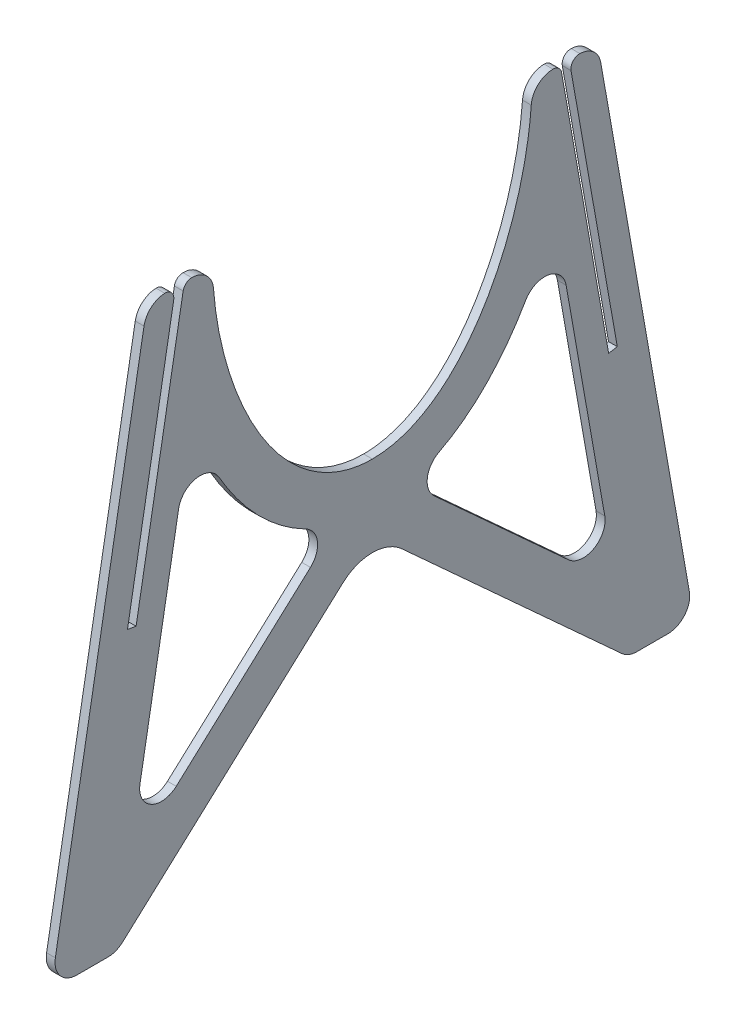
SolidWorks part; units mm, degrees
ref_plane "Front Plane" through (0, 0, 0) normal (0, 0, 1) x (1, 0, 0)
ref_plane "Top Plane" through (0, 0, 0) normal (0, 1, 0) x (1, 0, 0)
ref_plane "Right Plane" through (0, 0, 0) normal (1, 0, 0) x (0, 0, -1)
sketch "Sketch1" plane through (0, 0, 0) normal (1, 0, 0) x (0, 0, -1)
  line L0 (-36.5093, 0) -> (-51.5093, 0)
  line L1 (-51.5093, 0) -> (-73.5499, -124.9979)
  line L2 (-73.5499, -124.9979) -> (-58.5499, -124.9979)
  line L3 (0, -71.5821) -> (0, -56.5821)
  line L4 (-58.5499, -124.9979) -> (0, -71.5821)
  line L5 (-55.7055, -108.8666) -> (-8.1995, -65.5263)
  line L6 (-66.0499, -124.9979) -> (-44.0093, 0)
  line L7 (-36.5093, 0) -> (-58.5499, -124.9979)
  line L8 (-56.0144, -62.3253) -> (-54.0448, -62.6726)
  line L9 (-54.0448, -62.6726) -> (-42.9939, 0)
  line L10 (-56.0144, -62.3253) -> (-45.0248, 0)
  spline S0 degree 3 poles (-77.7959, -1999.3847) (-32.4836, 23.8711) (-36.7485, -12.4264) (-36.491, 1.5545) (-36.4661, 2.3494) (-36.4306, 3.1572) (-36.3845, 3.9779) (-36.3276, 4.8112) (-36.2596, 5.6568) (-36.1803, 6.5147) (-36.0895, 7.3844) (-35.9869, 8.2658) (-35.7244, 10.312) (-35.1824, 13.633) (-34.2081, 18.0418) (-32.9585, 22.5307) (-31.4871, 26.8758) (-29.7361, 31.19) (-27.7618, 35.3053) (-25.8567, 38.6677) (-24.1961, 41.2288) (-22.3532, 43.8233) (-19.9546, 46.7434) (-17.1663, 49.4666) (-14.8116, 51.366) (-12.8696, 52.7039) (-10.9306, 53.826) (-9.3257, 54.5881) (-8.076, 55.0896) (-7.1804, 55.4088) (-6.2832, 55.689) (-5.3849, 55.9304) (-4.4861, 56.1334) (-3.5872, 56.2984) (-2.6887, 56.4261) (-1.7912, 56.516) (18.7961, 57.7449) (5.3862, 31.1714) (1996.4181, 173.8153) knots -0.496353 -0.496353 -0.496353 -0.496353 0.010464 0.02111 0.03194 0.042952 0.054146 0.06552 0.077074 0.088806 0.100716 0.1128 0.125057 0.184996 0.250193 0.309425 0.375282 0.437501 0.499532 0.561635 0.595235 0.624194 0.69163 0.749302 0.783083 0.815122 0.84555 0.874512 0.887615 0.900555 0.913346 0.926005 0.938545 0.950983 0.963332 0.975609 0.987827 1.783802 1.783802 1.783802 1.783802 only from (-36.5093, 0) to (0, 56.5821)
  spline S1 degree 3 poles (-1998.8254, 118.855) (1.0133, 45.7594) (-12.3743, 56.9812) (0.9426, 56.5638) (1.4145, 56.5391) (1.8869, 56.5041) (2.3597, 56.459) (2.8328, 56.4036) (3.3061, 56.3379) (3.7796, 56.2618) (4.2531, 56.1753) (4.7267, 56.0782) (5.2003, 55.9706) (5.6737, 55.8523) (6.1469, 55.7234) (6.6198, 55.5837) (7.0925, 55.4333) (7.5646, 55.2719) (8.0363, 55.0998) (8.5074, 54.9167) (9.4771, 54.5166) (10.9487, 53.8166) (12.8926, 52.6895) (14.8396, 51.3453) (17.1949, 49.441) (19.9795, 46.7156) (22.3735, 43.7967) (24.2143, 41.2018) (25.8749, 38.6374) (27.7803, 35.2699) (29.7548, 31.1479) (31.5042, 26.8299) (32.9728, 22.484) (34.2165, 18.0065) (35.1851, 13.6164) (35.7638, 10.0694) (36.0753, 7.5493) (36.2369, 5.9585) (36.3605, 4.4083) (36.4465, 2.9002) (37.213, -19.7451) (26.3344, 23.0205) (116.0711, -1998.3604) knots -0.511405 -0.511405 -0.511405 -0.511405 0.006412 0.012834 0.019269 0.025719 0.032185 0.038671 0.045177 0.051706 0.058261 0.064843 0.071455 0.078099 0.084777 0.091492 0.098245 0.105039 0.111875 0.118757 0.125686 0.154729 0.185249 0.217392 0.25129 0.308883 0.376236 0.405202 0.438842 0.50101 0.563125 0.625443 0.691234 0.750428 0.815213 0.874806 0.897172 0.918949 0.940127 0.960698 0.980657 1.800718 1.800718 1.800718 1.800718 only from (0, 56.5821) to (36.5093, 0)
  spline S2 degree 3 poles (10989.6809, -475.2847) (-36.2394, -22.2542) (22.2831, -57.2917) (-0.9426, -56.5638) (-1.4145, -56.5391) (-1.8869, -56.5041) (-2.3597, -56.459) (-2.8328, -56.4036) (-3.3061, -56.3379) (-3.7796, -56.2618) (-4.2531, -56.1753) (-4.7267, -56.0782) (-5.2003, -55.9706) (-5.6737, -55.8523) (-6.1469, -55.7234) (-6.6198, -55.5837) (-7.0925, -55.4333) (-7.5646, -55.2719) (-8.0363, -55.0998) (-8.5074, -54.9167) (-9.4771, -54.5166) (-10.9487, -53.8166) (-12.8926, -52.6895) (-14.8396, -51.3453) (-17.1949, -49.441) (-19.9795, -46.7156) (-22.3735, -43.7967) (-24.2143, -41.2018) (-25.8749, -38.6374) (-27.7803, -35.2699) (-29.7548, -31.1479) (-31.5042, -26.8299) (-32.9728, -22.484) (-34.2165, -18.0065) (-35.1851, -13.6164) (-35.7638, -10.0694) (-36.0753, -7.5493) (-36.2369, -5.9585) (-36.3605, -4.4083) (-36.4465, -2.9002) (-37.7632, 36.0002) (-4.0465, -121.0006) (-537.3386, 10986.8499) knots -0.906271 -0.906271 -0.906271 -0.906271 0.006412 0.012834 0.019269 0.025719 0.032185 0.038671 0.045177 0.051706 0.058261 0.064843 0.071455 0.078099 0.084777 0.091492 0.098245 0.105039 0.111875 0.118757 0.125686 0.154729 0.185249 0.217392 0.25129 0.308883 0.376236 0.405202 0.438842 0.50101 0.563125 0.625443 0.691234 0.750428 0.815213 0.874806 0.897172 0.918949 0.940127 0.960698 0.980657 2.418461 2.418461 2.418461 2.418461 only from (0, -56.5821) to (-36.5093, 0)
  spline S3 degree 3 poles (77.7959, 1999.3847) (32.4836, -23.8711) (36.7485, 12.4264) (36.491, -1.5545) (36.4661, -2.3494) (36.4306, -3.1572) (36.3845, -3.9779) (36.3276, -4.8112) (36.2596, -5.6568) (36.1803, -6.5147) (36.0895, -7.3844) (35.9869, -8.2658) (35.7244, -10.312) (35.1824, -13.633) (34.2081, -18.0418) (32.9585, -22.5307) (31.4871, -26.8758) (29.7361, -31.19) (27.7618, -35.3053) (25.8567, -38.6677) (24.1961, -41.2288) (22.3532, -43.8233) (19.9546, -46.7434) (17.1663, -49.4666) (14.8116, -51.366) (12.8696, -52.7039) (10.9306, -53.826) (9.3257, -54.5881) (8.076, -55.0896) (7.1804, -55.4088) (6.2832, -55.689) (5.3849, -55.9304) (4.4861, -56.1334) (3.5872, -56.2984) (2.6887, -56.4261) (1.7912, -56.516) (-18.7961, -57.7449) (-5.3862, -31.1714) (-1996.4181, -173.8153) knots -0.496353 -0.496353 -0.496353 -0.496353 0.010464 0.02111 0.03194 0.042952 0.054146 0.06552 0.077074 0.088806 0.100716 0.1128 0.125057 0.184996 0.250193 0.309425 0.375282 0.437501 0.499532 0.561635 0.595235 0.624194 0.69163 0.749302 0.783083 0.815122 0.84555 0.874512 0.887615 0.900555 0.913346 0.926005 0.938545 0.950983 0.963332 0.975609 0.987827 1.783802 1.783802 1.783802 1.783802 only from (36.5093, 0) to (0, -56.5821)
  spline S4 degree 3 poles (36.5093, 0) (36.5093, -0.2338) (36.5066, -0.7092) (36.491, -1.5545) (36.4661, -2.3494) (36.4306, -3.1572) (36.3845, -3.9779) (36.3276, -4.8112) (36.2596, -5.6568) (36.1803, -6.5147) (36.0895, -7.3844) (35.9869, -8.2658) (35.7244, -10.312) (35.1824, -13.633) (34.2081, -18.0418) (32.9585, -22.5307) (31.4871, -26.8758) (29.7361, -31.19) (27.7618, -35.3053) (25.8567, -38.6677) (24.1961, -41.2288) (22.3532, -43.8233) (19.9546, -46.7434) (17.1663, -49.4666) (14.8116, -51.366) (12.8696, -52.7039) (10.9306, -53.826) (9.3257, -54.5881) (8.076, -55.0896) (7.1804, -55.4088) (6.2832, -55.689) (5.3849, -55.9304) (4.4861, -56.1334) (3.5872, -56.2984) (2.6887, -56.4261) (1.7912, -56.516) (0.8711, -56.5709) (0.2898, -56.5821) (0, -56.5821) knots 0 0 0 0 0.010464 0.02111 0.03194 0.042952 0.054146 0.06552 0.077074 0.088806 0.100716 0.1128 0.125057 0.184996 0.250193 0.309425 0.375282 0.437501 0.499532 0.561635 0.595235 0.624194 0.69163 0.749302 0.783083 0.815122 0.84555 0.874512 0.887615 0.900555 0.913346 0.926005 0.938545 0.950983 0.963332 0.975609 0.987827 1 1 1 1
  spline S5 degree 3 poles (0, -56.5821) (-0.1529, -56.5821) (-0.459, -56.579) (-0.9426, -56.5638) (-1.4145, -56.5391) (-1.8869, -56.5041) (-2.3597, -56.459) (-2.8328, -56.4036) (-3.3061, -56.3379) (-3.7796, -56.2618) (-4.2531, -56.1753) (-4.7267, -56.0782) (-5.2003, -55.9706) (-5.6737, -55.8523) (-6.1469, -55.7234) (-6.6198, -55.5837) (-7.0925, -55.4333) (-7.5646, -55.2719) (-8.0363, -55.0998) (-8.5074, -54.9167) (-9.4771, -54.5166) (-10.9487, -53.8166) (-12.8926, -52.6895) (-14.8396, -51.3453) (-17.1949, -49.441) (-19.9795, -46.7156) (-22.3735, -43.7967) (-24.2143, -41.2018) (-25.8749, -38.6374) (-27.7803, -35.2699) (-29.7548, -31.1479) (-31.5042, -26.8299) (-32.9728, -22.484) (-34.2165, -18.0065) (-35.1851, -13.6164) (-35.7638, -10.0694) (-36.0753, -7.5493) (-36.2369, -5.9585) (-36.3605, -4.4083) (-36.4465, -2.9002) (-36.4998, -1.3248) (-36.5093, -0.4326) (-36.5093, 0) knots 0 0 0 0 0.006412 0.012834 0.019269 0.025719 0.032185 0.038671 0.045177 0.051706 0.058261 0.064843 0.071455 0.078099 0.084777 0.091492 0.098245 0.105039 0.111875 0.118757 0.125686 0.154729 0.185249 0.217392 0.25129 0.308883 0.376236 0.405202 0.438842 0.50101 0.563125 0.625443 0.691234 0.750428 0.815213 0.874806 0.897172 0.918949 0.940127 0.960698 0.980657 1 1 1 1
  spline S6 degree 3 poles (0, 56.5821) (0.1529, 56.5821) (0.459, 56.579) (0.9426, 56.5638) (1.4145, 56.5391) (1.8869, 56.5041) (2.3597, 56.459) (2.8328, 56.4036) (3.3061, 56.3379) (3.7796, 56.2618) (4.2531, 56.1753) (4.7267, 56.0782) (5.2003, 55.9706) (5.6737, 55.8523) (6.1469, 55.7234) (6.6198, 55.5837) (7.0925, 55.4333) (7.5646, 55.2719) (8.0363, 55.0998) (8.5074, 54.9167) (9.4771, 54.5166) (10.9487, 53.8166) (12.8926, 52.6895) (14.8396, 51.3453) (17.1949, 49.441) (19.9795, 46.7156) (22.3735, 43.7967) (24.2143, 41.2018) (25.8749, 38.6374) (27.7803, 35.2699) (29.7548, 31.1479) (31.5042, 26.8299) (32.9728, 22.484) (34.2165, 18.0065) (35.1851, 13.6164) (35.7638, 10.0694) (36.0753, 7.5493) (36.2369, 5.9585) (36.3605, 4.4083) (36.4465, 2.9002) (36.4998, 1.3248) (36.5093, 0.4326) (36.5093, 0) knots 0 0 0 0 0.006412 0.012834 0.019269 0.025719 0.032185 0.038671 0.045177 0.051706 0.058261 0.064843 0.071455 0.078099 0.084777 0.091492 0.098245 0.105039 0.111875 0.118757 0.125686 0.154729 0.185249 0.217392 0.25129 0.308883 0.376236 0.405202 0.438842 0.50101 0.563125 0.625443 0.691234 0.750428 0.815213 0.874806 0.897172 0.918949 0.940127 0.960698 0.980657 1 1 1 1
  spline S7 degree 3 poles (-36.5093, 0) (-36.5093, 0.2338) (-36.5066, 0.7092) (-36.491, 1.5545) (-36.4661, 2.3494) (-36.4306, 3.1572) (-36.3845, 3.9779) (-36.3276, 4.8112) (-36.2596, 5.6568) (-36.1803, 6.5147) (-36.0895, 7.3844) (-35.9869, 8.2658) (-35.7244, 10.312) (-35.1824, 13.633) (-34.2081, 18.0418) (-32.9585, 22.5307) (-31.4871, 26.8758) (-29.7361, 31.19) (-27.7618, 35.3053) (-25.8567, 38.6677) (-24.1961, 41.2288) (-22.3532, 43.8233) (-19.9546, 46.7434) (-17.1663, 49.4666) (-14.8116, 51.366) (-12.8696, 52.7039) (-10.9306, 53.826) (-9.3257, 54.5881) (-8.076, 55.0896) (-7.1804, 55.4088) (-6.2832, 55.689) (-5.3849, 55.9304) (-4.4861, 56.1334) (-3.5872, 56.2984) (-2.6887, 56.4261) (-1.7912, 56.516) (-0.8711, 56.5709) (-0.2898, 56.5821) (0, 56.5821) knots 0 0 0 0 0.010464 0.02111 0.03194 0.042952 0.054146 0.06552 0.077074 0.088806 0.100716 0.1128 0.125057 0.184996 0.250193 0.309425 0.375282 0.437501 0.499532 0.561635 0.595235 0.624194 0.69163 0.749302 0.783083 0.815122 0.84555 0.874512 0.887615 0.900555 0.913346 0.926005 0.938545 0.950983 0.963332 0.975609 0.987827 1 1 1 1
  spline S8 degree 1 poles (0, -66.5821) (-46.5093, 0) knots 0 0 1 1 construction
  spline S9 degree 3 poles (0, -66.5821) (-2.2093, -66.5821) (-5.5468, -66.2358) (-9.8, -65.1209) (-13.8636, -63.6206) (-18.5017, -61.1271) (-24.903, -56.267) (-31.1991, -49.174) (-36.7969, -40.0093) (-40.9831, -30.4608) (-43.5092, -22.2748) (-44.9948, -15.5876) (-45.6929, -11.3436) (-46.1027, -7.9035) (-46.2932, -5.7346) (-46.4034, -3.9794) (-46.4645, -2.6063) (-46.5021, -1.2371) (-46.5093, -0.4204) (-46.5093, 0) knots 0 0 0 0 0.062484 0.093734 0.125 0.1875 0.25 0.375 0.5 0.625 0.75 0.8125 0.875 0.90625 0.9375 0.953125 0.96875 0.984375 1 1 1 1
  point P17 (0, 0)
  point P22 (-55.0296, -62.499)
  dimension "D1" = 15
  dimension "D2" = 100
  dimension "D3" = 15
  dimension "D5" = 10
  dimension "D6" = 2
  dimension "D4" = 10
extrude "Boss-Extrude1" add sketch "Sketch1" against normal blind 2 contours L7 S9 L1 L2 | S9 L7 L0 | S9 L3 S5 L7 | L4 S9 L5 L7 | L10 S9 L1 L2 L6 L8 | S9 L10 L0
fillet "Fillet1" radius 5 7 edges at (-1, 0, 51.5093) (-1, -28.3951, 41.5162) (-1, -124.9979, 58.5499) (-1, -124.9979, 73.5499) (-1, -108.8666, 55.7055) (-1, -65.5263, 8.1995)
mirror "Mirror2" about plane through (-2, 0, 0) normal (0, 0, -1) of bodies 101
fillet "Fillet2" radius 10 1 edges at (-1, -71.5821, 0)
fillet "Fillet3" radius 2 4 edges at (-1, 0, 45.0248) (-1, 0, 42.9939) (-1, 0, -42.9939) (-1, 0, -45.0248)
